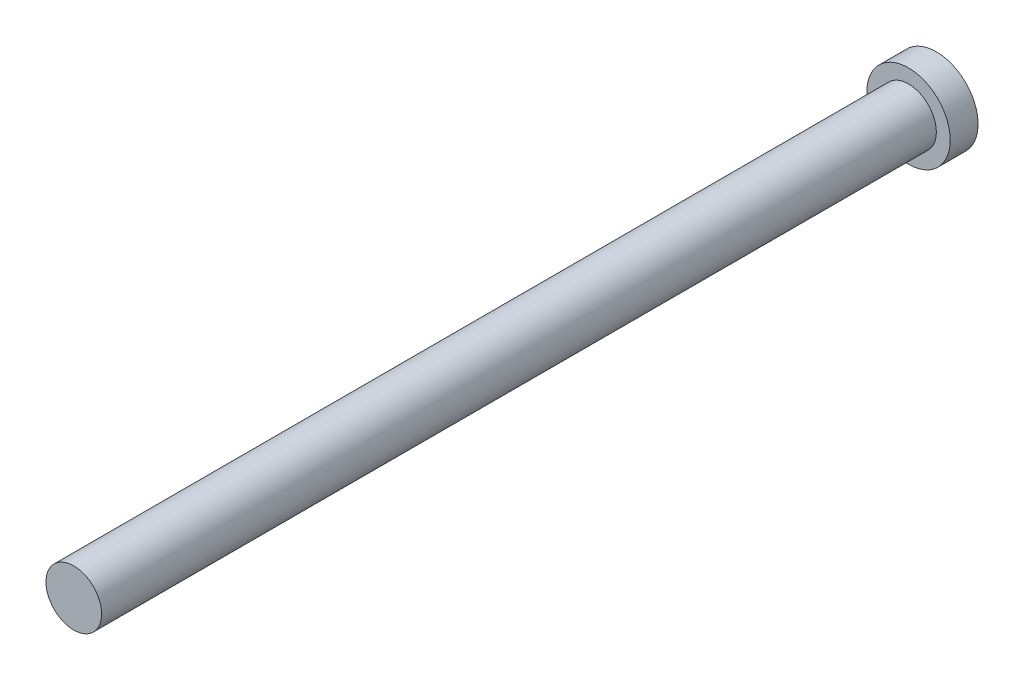
SolidWorks part; units mm, degrees
ref_plane "Front Plane" through (0, 0, 0) normal (0, 0, 1) x (1, 0, 0)
ref_plane "Top Plane" through (0, 0, 0) normal (0, 1, 0) x (1, 0, 0)
ref_plane "Right Plane" through (0, 0, 0) normal (1, 0, 0) x (0, 0, -1)
sketch "Sketch1" plane through (0, 0, 0) normal (0, 0, 1) x (1, 0, 0)
  circle A0 centre (0, 0) radius 2
  dimension "D1" = 4
extrude "Boss-Extrude1" add sketch "Sketch1" along normal blind 60
sketch "Sketch2" plane through (0, 0, 0) normal (0, 0, -1) x (-1, 0, 0)
  circle A0 centre (0, 0) radius 3
  dimension "D1" = 6
extrude "Boss-Extrude2" add sketch "Sketch2" along normal blind 2
